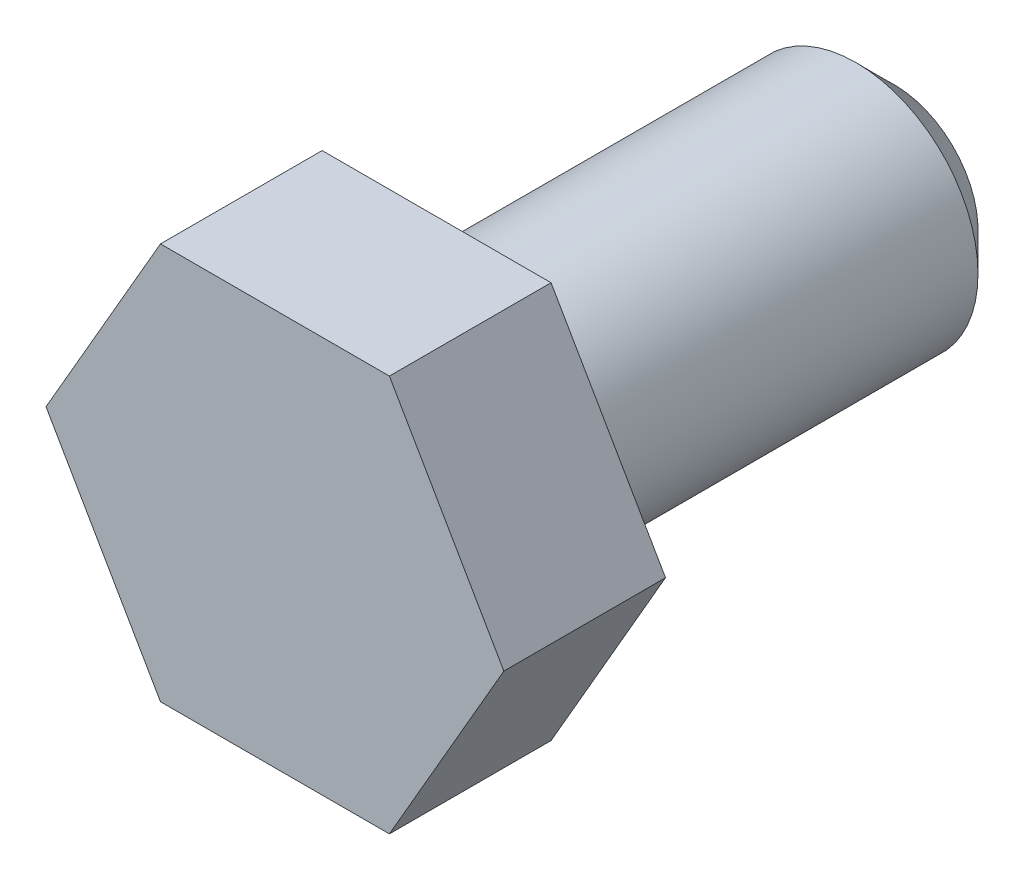
SolidWorks part; units mm, degrees
ref_plane "Plane1" through (0, 0, 0) normal (0, 0, 1) x (1, 0, 0)
ref_plane "MSC_PF1" through (0, 0, 0) normal (0, 1, 0) x (1, 0, 0)
ref_plane "Plane3" through (0, 0, 0) normal (1, 0, 0) x (0, 0, -1)
sketch "Sketch1" plane through (0, 0, 0) normal (0, 0, 1) x (1, 0, 0)
  line L0 (0, 0) -> (1, 0) construction
  line L1 (-3.7528, 6.5) -> (3.7528, 6.5)
  line L2 (-3.7528, -6.5) -> (3.7528, -6.5)
  line L3 (3.7528, 6.5) -> (7.5056, 0)
  line L4 (7.5056, 0) -> (3.7528, -6.5)
  line L5 (-3.7528, 6.5) -> (-7.5056, 0)
  line L6 (-7.5056, 0) -> (-3.7528, -6.5)
  circle A0 centre (0, 0) radius 6.5 construction
  dimension "P" = 1
  dimension "s" = 13
extrude "Base-Extrude" add sketch "Sketch1" along normal blind 5.3
sketch "Sketch3" plane through (0, 0, 0) normal (0, 0, -1) x (-1, 0, 0)
  circle A0 centre (0, 0) radius 4
  dimension "_d" = 8
extrude "Boss-Extrude1" add sketch "Sketch3" along normal blind 15
cosmetic thread "Условное изображение резьбы2" parameters "D2"=7
chamfer "Chamfer1" distance 1.25 angle 45 1 edges at (-4, 0, -15)
